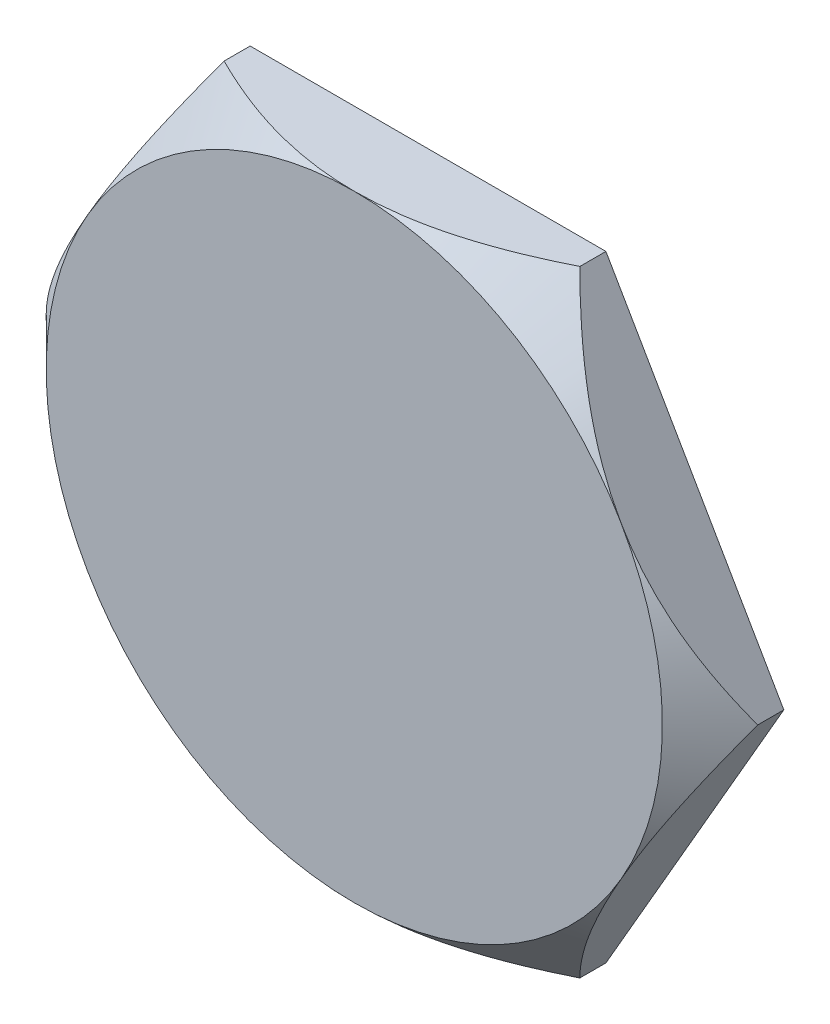
SolidWorks part; units mm, degrees
ref_plane "Front Plane" through (0, 0, 0) normal (0, 0, 1) x (1, 0, 0)
ref_plane "Top Plane" through (0, 0, 0) normal (0, 1, 0) x (1, 0, 0)
ref_plane "Right Plane" through (0, 0, 0) normal (1, 0, 0) x (0, 0, -1)
sketch "Sketch1" plane through (0, 0, 0) normal (0, 0, 1) x (1, 0, 0)
  line L1 (21.7125, -37.6071) -> (43.4249, 0)
  line L2 (43.4249, 0) -> (21.7125, 37.6071)
  line L3 (21.7125, 37.6071) -> (-21.7125, 37.6071)
  line L4 (-21.7125, 37.6071) -> (-43.4249, 0)
  line L5 (-43.4249, 0) -> (-21.7125, -37.6071)
  line L6 (-21.7125, -37.6071) -> (21.7125, -37.6071)
  circle A0 centre (0, 0) radius 37.6071 construction
extrude "Boss-Extrude1" add sketch "Sketch1" along normal mid plane 9
sketch "Sketch2" plane through (0, 0, 4.5) normal (0, 0, 1) x (1, 0, 0)
  line L0 (-21.7125, 37.6071) -> (-43.4249, 0) construction
  circle A0 centre (0, 0) radius 37.6071
extrude "Cut-Extrude1" cut sketch "Sketch2" against normal through all draft 45 flip side to cut
